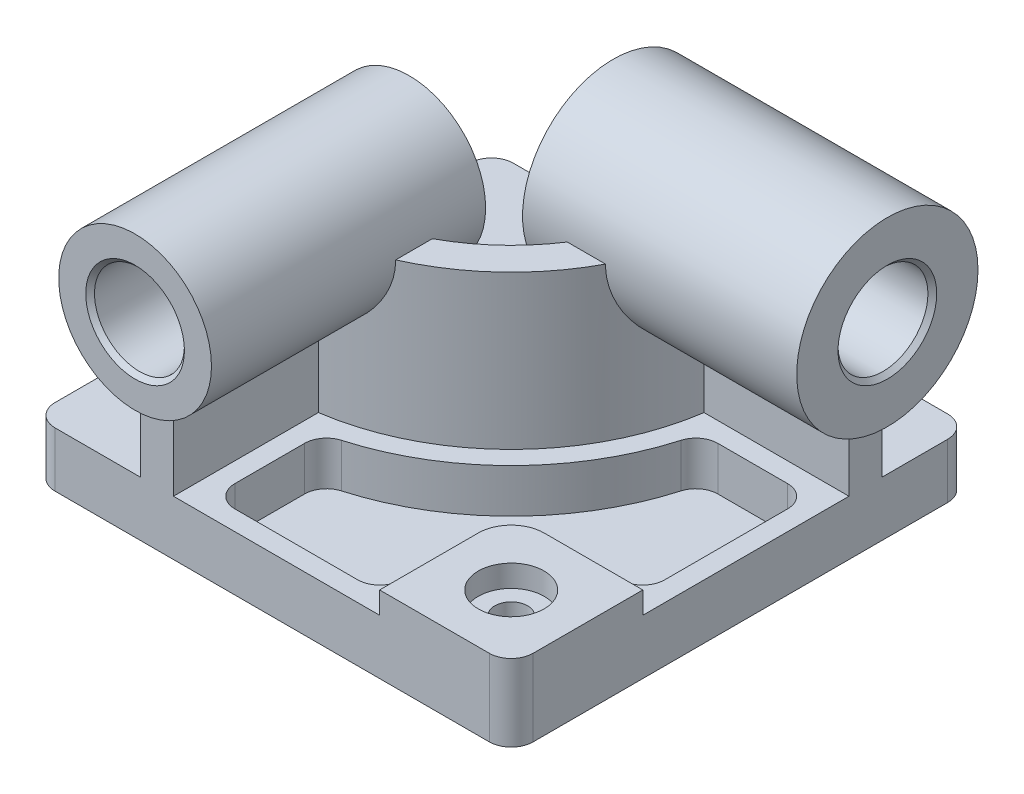
SolidWorks part; units mm, degrees
material "Alloy Steel"
ref_plane "Front Plane" through (0, 0, 0) normal (0, 0, 1) x (1, 0, 0)
ref_plane "Top Plane" through (0, 0, 0) normal (0, 1, 0) x (1, 0, 0)
ref_plane "Right Plane" through (0, 0, 0) normal (1, 0, 0) x (0, 0, -1)
sketch "Sketch1" plane through (0, 0, 0) normal (0, 1, 0) x (1, 0, 0)
  line L0 (0, 0) -> (0, -169) construction
  line L1 (-39, 40) -> (159, 40)
  line L2 (-49, 30) -> (-49, -159)
  line L3 (-39, -169) -> (159, -169)
  line L4 (169, 30) -> (169, -159)
  line L6 (21.1729, -100.3509) -> (22.0551, -100.3509) construction
  line L8 (0, 0) -> (169, 0) construction
  arc A0 (-39, 40) -> (-49, 30) centre (-39, 30) ccw
  arc A1 (-49, -159) -> (-39, -169) centre (-39, -159) ccw
  arc A2 (159, -169) -> (169, -159) centre (159, -159) ccw
  arc A3 (159, 40) -> (169, 30) centre (159, 30) cw
  dimension "D5" = 10
  dimension "D1" = 169
  dimension "D2" = 169
  dimension "D3" = 209
  dimension "D4" = 218
extrude "Boss-Extrude1" add sketch "Sketch1" along normal blind 25
sketch "Sketch2" plane through (0, 25, 0) normal (0, 1, 0) x (1, 0, 0)
  line L0 (0, -89) -> (0, -169)
  line L1 (-39, -169) -> (159, -169) construction
  line L2 (89, 0) -> (169, 0)
  line L3 (169, -159) -> (169, 30) construction
  line L4 (15, -102.9126) -> (15, -169)
  line L5 (102.9126, -15) -> (169, -15)
  line L6 (169, 0) -> (169, -15)
  line L7 (0, -169) -> (15, -169)
  arc A0 (0, -89) -> (89, 0) centre (0, 0) ccw
  arc A1 (15, -102.9126) -> (102.9126, -15) centre (0, 0) ccw
  dimension "D1" = 80
  dimension "D2" = 15
extrude "Boss-Extrude2" add sketch "Sketch2" along normal blind 95 from surface at -25 starting at face at (60, 0, 64.5)
sketch "Sketch3" plane through (0, 25, 0) normal (0, 1, 0) x (1, 0, 0)
  line L0 (15, -169) -> (159, -169) construction
  line L1 (124, -109) -> (169, -109)
  line L2 (109, -124) -> (109, -169)
  line L3 (109, -169) -> (159, -169)
  line L4 (169, -109) -> (169, -159)
  line L5 (169, -159) -> (169, -15) construction
  arc A0 (159, -169) -> (169, -159) centre (159, -159) ccw construction
  arc A1 (159, -169) -> (169, -159) centre (159, -159) ccw
  arc A2 (124, -109) -> (109, -124) centre (124, -124) ccw
  dimension "D3" = 15
  dimension "D1" = 60
  dimension "D2" = 60
extrude "Boss-Extrude3" add sketch "Sketch3" along normal blind 10
hole_wizard "CBORE for M8 Hex Head Bolt1" positions "Sketch5" profile "Sketch4" counterbore size "M8" standard "ANSI Metric" end condition through all
sketch "Sketch5" plane through (0, 35, 0) normal (0, 1, 0) x (1, 0, 0)
  line L0 (109, -169) -> (159, -169) construction
  line L2 (169, -159) -> (169, -109) construction
  point P0 (139, -139)
  dimension "D1" = 30
  dimension "D2" = 30
sketch "Sketch4" plane through (139, 35, 139) normal (1, 0, 0) x (0, 0, 1)
  line L0 (0, 0) -> (0, 35)
  line L1 (0, 35) -> (7.5, 35)
  line L3 (7.5, 35) -> (7.5, 10)
  line L4 (7.5, 10) -> (15, 10)
  line L5 (15, 10) -> (15, 0)
  line L7 (15, 0) -> (0, 0)
  line L11 (0, -6.35) -> (0, 107.95) construction
  dimension "Thru Hole Dia." = 15
  dimension "Thru Hole Depth" = 35
  dimension "C'Bore Dia." = 30
  dimension "C'Bore Depth" = 10
sketch "Sketch6" plane through (0, 25, 0) normal (0, 1, 0) x (1, 0, 0)
  line L6 (100, -160) -> (100, -124)
  line L7 (100, -150) -> (100, -124)
  line L8 (124, -100) -> (160, -100)
  line L9 (124, -100) -> (150, -100)
  line L10 (160, -24) -> (110.4219, -24)
  line L11 (150, -24) -> (118.2074, -24)
  line L12 (24, -160) -> (100, -160)
  line L13 (24, -110.4219) -> (24, -160)
  line L14 (24, -118.2074) -> (24, -150)
  line L15 (160, -100) -> (160, -24)
  line L18 (34, -160) -> (90, -160)
  line L21 (160, -90) -> (160, -34)
  arc A0 (160, -90) -> (150, -100) centre (150, -90) cw
  arc A1 (100, -150) -> (90, -160) centre (90, -150) cw
  arc A2 (24, -118.2074) -> (31.2358, -108.5971) centre (34, -118.2074) cw
  arc A3 (108.5971, -31.2358) -> (118.2074, -24) centre (118.2074, -34) cw
  arc A4 (124, -100) -> (100, -124) centre (124, -124) ccw
  arc A5 (24, -110.4219) -> (110.4219, -24) centre (0, 0) ccw
  arc A6 (124, -100) -> (100, -124) centre (124, -124) ccw
  arc A7 (31.2358, -108.5971) -> (108.5971, -31.2358) centre (0, 0) ccw
  arc A8 (160, -34) -> (150, -24) centre (150, -34) ccw
  arc A9 (34, -160) -> (24, -150) centre (34, -150) cw
  dimension "D2" = 10
  dimension "D3" = 10
  dimension "D1" = 9
extrude "Cut-Extrude1" cut sketch "Sketch6" against normal offset from surface (20 mm away) 5 up to face at (139, 0, 146.5)
sketch "Sketch7" plane through (0, 0, 169) normal (0, 0, 1) x (1, 0, 0)
  line L0 (0, 95) -> (15, 95) construction
  circle A0 centre (7.5, 95) radius 34.8333
  dimension "D1" = 69.6667
extrude "Boss-Extrude4" add sketch "Sketch7" against normal blind 125 from offset 10
sketch "Sketch8" plane through (169, 0, 0) normal (1, 0, 0) x (0, 0, -1)
  line L0 (-15, 95) -> (0, 95) construction
  circle A0 centre (-7.5, 95) radius 41.3333
  dimension "D1" = 82.6667
extrude "Boss-Extrude5" add sketch "Sketch8" against normal blind 125 from offset 10
sketch "Sketch9" plane through (0, 0, 179) normal (0, 0, 1) x (1, 0, 0)
  circle A0 centre (7.5, 95) radius 20.5
  dimension "D1" = 41
extrude "Cut-Extrude2" cut sketch "Sketch9" against normal up to next
sketch "Sketch10" plane through (179, 0, 0) normal (1, 0, 0) x (0, 0, -1)
  circle A0 centre (-7.5, 95) radius 20.5
  dimension "D1" = 41
extrude "Cut-Extrude3" cut sketch "Sketch10" against normal up to next
chamfer "Chamfer1" distance 2 angle 45 4 edges at (54, 95, -13) (28, 95, 54) (179, 95, -13) (28, 95, 179)
equation "\"A\" = 209"
equation "\"D1@Sketch1\"=\"C\""
equation "\"D2@Sketch1\"=\"C\""
equation "\"B\" = 218"
equation "\"D3@Sketch1\"=\"A\""
equation "\"C\" = 169"
equation "\"D4@Sketch1\"=\"B\""
equation "\"D1@Sketch7\"=\"X\""
equation "\"D\" = 125"
equation "\"D1@Boss-Extrude4\"=\"D\""
equation "\"D1@Sketch8\"=\"Y\""
equation "\"D1@Boss-Extrude5\"=\"D\""
equation "\"E\" = 41"
equation "\"D1@Sketch9\"=\"E\""
equation "\"D1@Sketch10\"=\"E\""
equation "\"X\"= \"A\" / 3"
equation "\"Y\"= \"B\" / 3 + 10"
